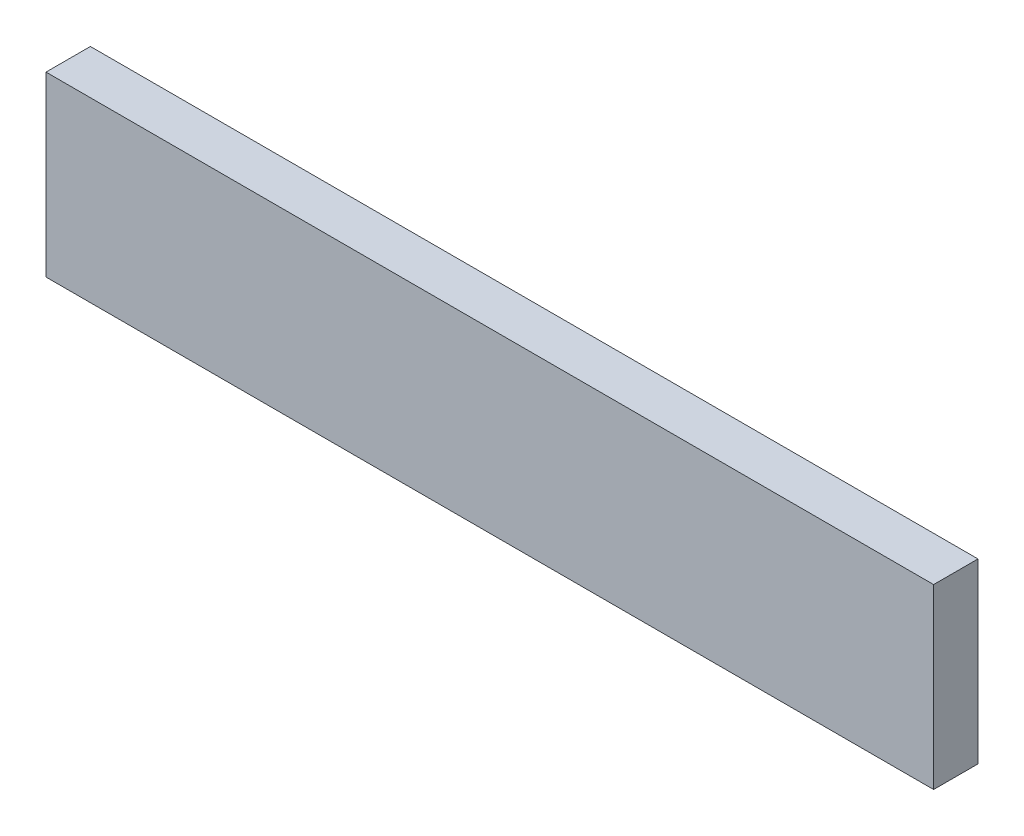
SolidWorks part; units mm, degrees
ref_plane "Alzado" through (0, 0, 0) normal (0, 0, 1) x (1, 0, 0)
ref_plane "Planta" through (0, 0, 0) normal (0, 1, 0) x (1, 0, 0)
ref_plane "Vista lateral" through (0, 0, 0) normal (1, 0, 0) x (0, 0, -1)
sketch "Croquis1" plane through (0, 0, 0) normal (0, 0, 1) x (1, 0, 0)
  line L1 (-452.1653, 185.3877) -> (547.8347, 185.3877)
  line L2 (-452.1653, 185.3877) -> (-452.1653, -14.6123)
  line L3 (-452.1653, -14.6123) -> (547.8347, -14.6123)
  line L4 (547.8347, 185.3877) -> (547.8347, -14.6123)
  dimension "D1" = 1000
  dimension "D2" = 200
extrude "Saliente-Extruir1" add sketch "Croquis1" along normal blind 50
